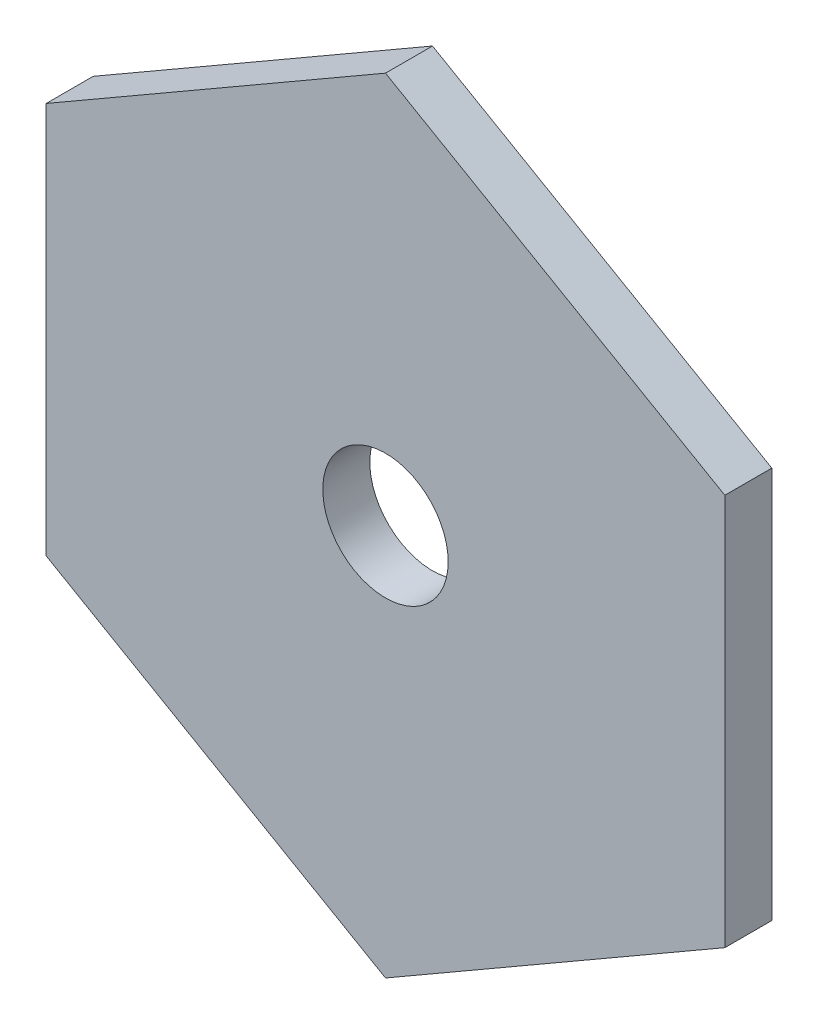
SolidWorks part; units mm, degrees
ref_plane "Front Plane" through (0, 0, 0) normal (0, 0, 1) x (1, 0, 0)
ref_plane "Top Plane" through (0, 0, 0) normal (0, 1, 0) x (1, 0, 0)
ref_plane "Right Plane" through (0, 0, 0) normal (1, 0, 0) x (0, 0, -1)
sketch "Sketch1" plane through (0, 0, 0) normal (0, 0, 1) x (1, 0, 0)
  line L1 (0, 25) -> (-21.6506, 12.5)
  line L2 (-21.6506, 12.5) -> (-21.6506, -12.5)
  line L3 (-21.6506, -12.5) -> (0, -25)
  line L4 (0, -25) -> (21.6506, -12.5)
  line L5 (21.6506, -12.5) -> (21.6506, 12.5)
  line L6 (21.6506, 12.5) -> (0, 25)
  circle A1 centre (0, 0) radius 21.6506 construction
extrude "Boss-Extrude1" add sketch "Sketch1" along normal blind 3
sketch "Sketch2" plane through (0, 0, 3) normal (0, 0, 1) x (1, 0, 0)
  circle A0 centre (0, 0) radius 4
  dimension "D1" = 8
extrude "Cut-Extrude1" cut sketch "Sketch2" against normal blind 3
